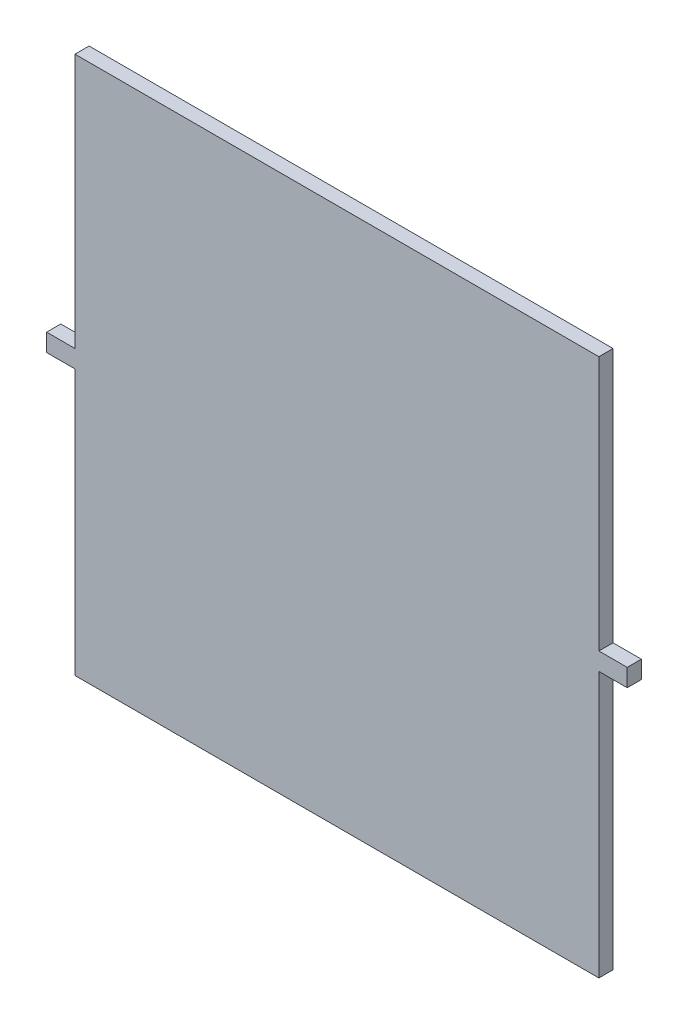
SolidWorks part; units mm, degrees
ref_plane "Спереди" through (0, 0, 0) normal (0, 0, 1) x (1, 0, 0)
ref_plane "Сверху" through (0, 0, 0) normal (0, 1, 0) x (1, 0, 0)
ref_plane "Справа" through (0, 0, 0) normal (1, 0, 0) x (0, 0, -1)
sketch "Эскиз1" plane through (0, 0, 0) normal (0, 0, 1) x (1, 0, 0)
  line L0 (0, 75) -> (148, 75) construction
  line L1 (0, 0) -> (148, 0)
  line L2 (0, 0) -> (0, 152)
  line L3 (0, 152) -> (148, 152)
  line L4 (148, 0) -> (148, 152)
  line L5 (148, 80) -> (156, 80)
  line L6 (148, 80) -> (148, 75)
  line L7 (148, 75) -> (156, 75)
  line L8 (156, 80) -> (156, 75)
  line L9 (0, 80) -> (-8, 80)
  line L10 (0, 80) -> (0, 75)
  line L11 (0, 75) -> (-8, 75)
  line L12 (-8, 80) -> (-8, 75)
  dimension "D1" = 152
  dimension "D2" = 148
  dimension "D3" = 75
  dimension "D4" = 5
  dimension "D5" = 5
  dimension "D6" = 8
  dimension "D7" = 8
extrude "Бобышка-Вытянуть1" add sketch "Эскиз1" along normal blind 4 contours L2 L0 L4 L3 | L9 L12 L11 L2 | L0 L2 L1 L4 | L8 L5 L4 L7
sketch "Эскиз2" plane through (-8, 0, 0) normal (-1, 0, 0) x (0, 0, 1)
  line L0 (2, 80) -> (2, 75) construction
  line L1 (4, 80) -> (0, 80) construction
  line L2 (4, 75) -> (0, 75) construction
  circle A0 centre (2, 77.5) radius 1.1827 construction
